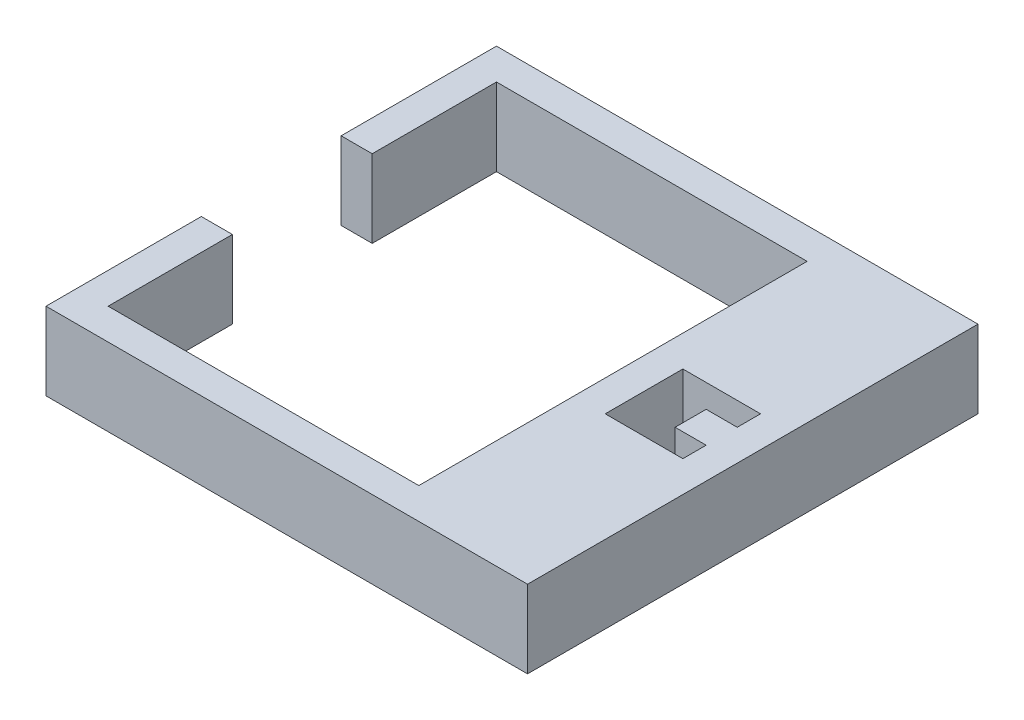
SolidWorks part; units mm, degrees
ref_plane "Front Plane" through (0, 0, 0) normal (0, 0, 1) x (1, 0, 0)
ref_plane "Top Plane" through (0, 0, 0) normal (0, 1, 0) x (1, 0, 0)
ref_plane "Right Plane" through (0, 0, 0) normal (1, 0, 0) x (0, 0, -1)
sketch "Sketch1" plane through (0, 0, 0) normal (0, 1, 0) x (1, 0, 0)
  line L0 (-43.9377, -3.6119) -> (46.0623, -3.6119)
  line L1 (-23.9377, 21.3881) -> (26.0623, 21.3881)
  line L2 (-23.9377, 21.3881) -> (-23.9377, -28.6119)
  line L3 (-23.9377, -28.6119) -> (26.0623, -28.6119)
  line L4 (26.0623, 21.3881) -> (26.0623, -28.6119)
  line L5 (-43.9377, 41.3881) -> (46.0623, 41.3881)
  line L6 (-43.9377, 41.3881) -> (-43.9377, -48.6119)
  line L7 (-43.9377, -48.6119) -> (46.0623, -48.6119)
  line L8 (46.0623, 41.3881) -> (46.0623, -48.6119)
  line L9 (26.0623, 6.3881) -> (6.0623, 6.3881)
  line L10 (26.0623, 6.3881) -> (26.0623, -13.6119)
  line L11 (26.0623, -13.6119) -> (6.0623, -13.6119)
  line L12 (6.0623, 6.3881) -> (6.0623, -13.6119)
  line L25 (-263.9377, 141.3881) -> (46.0623, 141.3881)
  line L26 (-263.9377, 141.3881) -> (-263.9377, 175.8198)
  line L27 (-243.9377, 121.3881) -> (-43.9377, 121.3881)
  line L28 (46.0623, 141.3881) -> (46.0623, 95.5762)
  line L29 (-65.7423, 141.3881) -> (46.0623, 141.3881)
  line L30 (-43.9377, 121.3881) -> (-43.9377, 41.3881)
  line L31 (-43.9377, 41.3881) -> (46.0623, 41.3881)
  line L32 (46.0623, 141.3881) -> (46.0623, 41.3881)
  line L33 (-263.9377, 141.3881) -> (-275.2755, 141.3881)
  line L34 (-263.9377, 141.3881) -> (-263.9377, 41.3881)
  line L35 (-263.9377, 41.3881) -> (-243.9377, 41.3881)
  line L36 (-243.9377, 121.3881) -> (-243.9377, 41.3881)
  line L37 (-263.9377, -48.6119) -> (-243.9377, -48.6119)
  line L38 (-263.9377, -148.6119) -> (-263.9377, -48.6119)
  line L39 (-243.9377, -128.6119) -> (-243.9377, -48.6119)
  line L40 (-243.9377, -128.6119) -> (-43.9377, -128.6119)
  line L41 (-263.9377, -148.6119) -> (46.0623, -148.6119)
  line L42 (46.0623, -148.6119) -> (46.0623, -48.6119)
  line L43 (-43.9377, -128.6119) -> (-43.9377, -48.6119)
  point P32 (-436.597, -160.6949)
  point P34 (18.29, 81.3214)
  dimension "D1" = 50
  dimension "D2" = 50
  dimension "D3" = 90
  dimension "D4" = 90
  dimension "D5" = 20
  dimension "D6" = 20
  dimension "D7" = 20
  dimension "D8" = 20
  dimension "D9" = 15
  dimension "D10" = 100
  dimension "D12" = 100
  dimension "D13" = 20
  dimension "D14" = 80
  dimension "D15" = 90
  dimension "D11" = 200
  dimension "D16" = 0
extrude "Boss-Extrude2" add sketch "Sketch1" along normal blind 50 contours L36 L27 L30 L5 L32 L28 L25 L34 L35 | L43 L40 L39 L37 L38 L41 L42 L7 | L8 L0 L4 L3 L2 L6 L7 | L8 L5 L6 L0 L2 L1 L4 | L9 L12 L0 L4
equation "\"ScannerWidth\"= 800"
equation "\"ScannerLength\"= 400"
equation "\"SpineLength\"= 100"
equation "\"ScannerThickness\"= 50"
equation "\"ScannerHeight\" = 50"
equation "\"SpineWidth\"= 100"
equation "\"TrainWidth\"= 40"
equation "\"TrainLength\"=20"
equation "\"Armwidth\"= 50"
equation "\"Armlength\"=1000"
equation "\"RailWidth\"= 20"
equation "\"RailLength\"= 650"
equation "\"RailDepth\"=20"
equation "\"D1@Sketch1\"=\"ScannerThickness\""
equation "\"D2@Sketch1\"=\"ScannerThickness\""
equation "\"CarThickness\"= 20"
equation "\"D3@Sketch1\"=\"ScannerHeight\"+\"CarThickness\"*2"
equation "\"D4@Sketch1\"=\"ScannerThickness\"+\"CarThickness\"*2"
equation "\"D6@Sketch1\"=\"CarThickness\""
equation "\"D7@Sketch1\"=\"RailDepth\""
equation "\"D8@Sketch1\"=\"RailWidth\""
equation "\"D9@Sketch1\"=(\"ScannerThickness\"-\"RailWidth\")/2"
equation "\"CarWidth\"=50"
equation "\"ArmScanLength\"= 200"
equation "\"ArmScanWidth\"= 50"
equation "\"ArmScanHeight\"= 100"
equation "\"D10@Sketch1\"=\"ArmScanHeight\""
equation "\"D12@Sketch1\"=\"ArmScanHeight\""
equation "\"ArmScanThickness\"= 20"
equation "\"D13@Sketch1\"=\"ArmScanThickness\""
equation "\"D14@Sketch1\"=\"D12@Sketch1\"-\"ArmScanThickness\""
equation "\"D15@Sketch1\"=\"D3@Sketch1\""
equation "\"D11@Sketch1\"=\"ArmScanLength\""
equation "\"D16@Sketch1\"=0"
equation "\"D1@Boss-Extrude2\"=\"CarWidth\""
